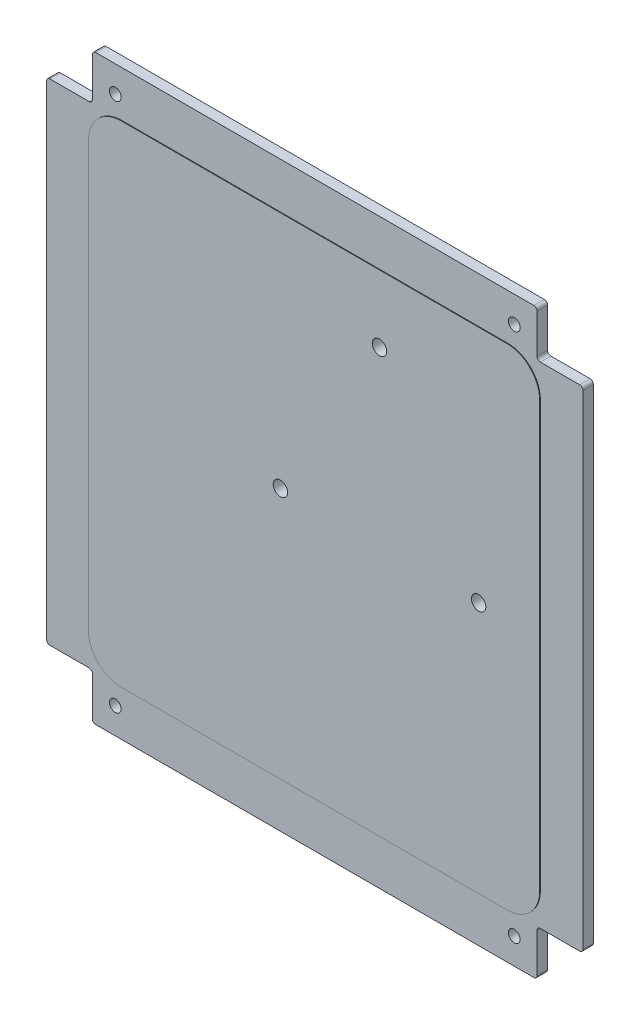
SolidWorks part; units mm, degrees
material "PET"
ref_plane "Front Plane" through (0, 0, 0) normal (0, 0, 1) x (1, 0, 0)
ref_plane "Top Plane" through (0, 0, 0) normal (0, 1, 0) x (1, 0, 0)
ref_plane "Right Plane" through (0, 0, 0) normal (1, 0, 0) x (0, 0, -1)
sketch "Sketch1" plane through (0, 0, 0) normal (0, 0, 1) x (1, 0, 0)
  line L0 (-34, 44) -> (-34, 38)
  line L1 (-33.5, -44.5) -> (33.5, -44.5)
  line L2 (-41, 37) -> (-41, -37)
  line L3 (-33.5, 44.5) -> (33.5, 44.5)
  line L4 (41, -37) -> (41, 37)
  line L5 (34, -44) -> (34, -38)
  line L6 (34.5, -37.5) -> (40.5, -37.5)
  line L7 (-34.5, 37.5) -> (-40.5, 37.5)
  line L8 (34, 44) -> (34, 38)
  line L9 (34.5, 37.5) -> (40.5, 37.5)
  line L10 (-40.5, -37.5) -> (-34.5, -37.5)
  line L11 (-34, -38) -> (-34, -44)
  line L12 (-34.5, -38) -> (34.5, 38) construction
  line L13 (34.5, -38) -> (-34.5, 38) construction
  arc A0 (-33.5, 44.5) -> (-34, 44) centre (-33.5, 44) ccw
  arc A1 (33.5, 44.5) -> (34, 44) centre (33.5, 44) cw
  arc A2 (34, 38) -> (34.5, 37.5) centre (34.5, 38) ccw
  arc A3 (40.5, 37.5) -> (41, 37) centre (40.5, 37) cw
  arc A4 (33.5, -44.5) -> (34, -44) centre (33.5, -44) ccw
  arc A5 (34.5, -37.5) -> (34, -38) centre (34.5, -38) ccw
  arc A6 (40.5, -37.5) -> (41, -37) centre (40.5, -37) ccw
  arc A7 (-34, -44) -> (-33.5, -44.5) centre (-33.5, -44) ccw
  arc A8 (-34, -38) -> (-34.5, -37.5) centre (-34.5, -38) ccw
  arc A9 (-41, -37) -> (-40.5, -37.5) centre (-40.5, -37) ccw
  arc A10 (-40.5, 37.5) -> (-41, 37) centre (-40.5, 37) ccw
  arc A11 (-34.5, 37.5) -> (-34, 38) centre (-34.5, 38) ccw
  point P0 (0, 0)
  dimension "D4" = 0.5
  dimension "D1" = 7
  dimension "D2" = 7
  dimension "D3" = 7
  dimension "D5" = 7
  dimension "D6" = 7
  dimension "D7" = 7
  dimension "D8" = 7
  dimension "D9" = 7
  dimension "D10" = 89
  dimension "D11" = 82
extrude "Boss-Extrude1" add sketch "Sketch1" along normal blind 1.6
sketch "Esboço1" plane through (0, 0, 1.6) normal (0, 0, 1) x (1, 0, 0)
  line L1 (-29.5, -37.5) -> (29.5, -37.5)
  line L2 (-34.5, -32.5) -> (-34.5, 32.5)
  line L3 (-29.5, 37.5) -> (29.5, 37.5)
  line L4 (34.5, -32.5) -> (34.5, 32.5)
  line L5 (-29.5, -32.5) -> (29.5, 32.5) construction
  line L6 (-29.5, 32.5) -> (29.5, -32.5) construction
  arc A0 (-34.5, 32.5) -> (-29.5, 37.5) centre (-29.5, 32.5) cw
  arc A1 (29.5, 37.5) -> (34.5, 32.5) centre (29.5, 32.5) cw
  arc A2 (34.5, -32.5) -> (29.5, -37.5) centre (29.5, -32.5) cw
  arc A3 (-29.5, -37.5) -> (-34.5, -32.5) centre (-29.5, -32.5) cw
  point P0 (0, 0)
  dimension "D1" = 5
  dimension "D2" = 69
  dimension "D3" = 75
extrude "Boss-Extrude2" add sketch "Esboço1" along normal blind 0.1
hole_wizard "M1.6 Hole1-FixingStructure" positions "Sketch3" profile "Sketch2" hole size "M1.6" standard "DIN"
sketch "Sketch3" plane through (0, 0, 0) normal (0, 0, -1) x (-1, 0, 0)
  line L0 (-33.5, 44.5) -> (33.5, 44.5) construction
  line L1 (33.5, -44.5) -> (-33.5, -44.5) construction
  line L2 (-41, -37) -> (-41, 37) construction
  line L3 (41, 37) -> (41, -37) construction
  point P0 (-30.5, 40.5)
  point P2 (30.5, 40.5)
  point P4 (-30.5, -40.5)
  point P6 (30.5, -40.5)
  dimension "D1" = 4
  dimension "D2" = 4
  dimension "D3" = 10.5
  dimension "D4" = 10.5
sketch "Sketch2" plane through (30.5, 40.5, 0) normal (1, 0, 0) x (0, 1, 0)
  line L0 (0, 0) -> (0, 200.5408)
  line L1 (0, 200.5408) -> (0.9, 200)
  line L2 (0.9, 200) -> (0.9, 0)
  line L5 (0.9, 0) -> (0, 0)
  line L10 (0, 200.5408) -> (-0.9, 200) construction
  line L11 (0, -6.35) -> (0, 107.95) construction
  dimension "Hole Dia." = 1.8
  dimension "Hole Depth" = 200
  dimension "Drill Angle" = 118
sketch "Sketch4" plane through (0, 0, 1.7) normal (0, 0, 1) x (1, 0, 0)
  circle A0 centre (25.1554, 1) radius 1.1 construction
  circle A1 centre (10, 27.25) radius 1.1 construction
  circle A2 centre (-5.1554, 1) radius 1.1 construction
  circle A3 centre (25.1554, 1) radius 1.1
  circle A4 centre (10, 27.25) radius 1.1
  circle A5 centre (-5.1554, 1) radius 1.1
extrude "Cut-Extrude1" cut sketch "Sketch4" against normal up to surface (1.7 mm away) up to face at (29.6, 40.5, 0)
